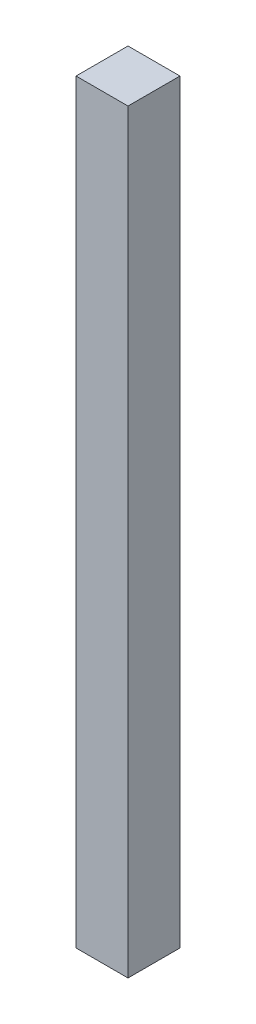
SolidWorks part; units mm, degrees
ref_plane "Front Plane" through (0, 0, 0) normal (0, 0, 1) x (1, 0, 0)
ref_plane "Top Plane" through (0, 0, 0) normal (0, 1, 0) x (1, 0, 0)
ref_plane "Right Plane" through (0, 0, 0) normal (1, 0, 0) x (0, 0, -1)
sketch "Sketch1" plane through (0, 0, 0) normal (0, 1, 0) x (1, 0, 0)
  line L1 (0, 0) -> (20, 0)
  line L2 (0, 0) -> (0, -20)
  line L3 (0, -20) -> (20, -20)
  line L4 (20, 0) -> (20, -20)
extrude "Boss-Extrude1" add sketch "Sketch1" along normal up to surface (290.5605 mm away)
